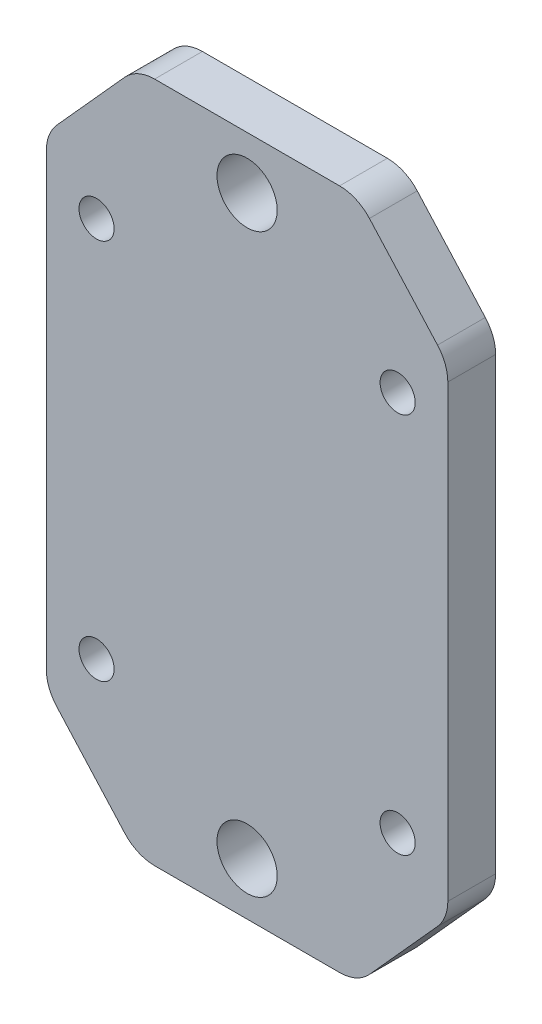
SolidWorks part; units mm, degrees
ref_plane "Front Plane" through (0, 0, 0) normal (0, 0, 1) x (1, 0, 0)
ref_plane "Top Plane" through (0, 0, 0) normal (0, 1, 0) x (1, 0, 0)
ref_plane "Right Plane" through (0, 0, 0) normal (1, 0, 0) x (0, 0, -1)
sketch "Sketch1" plane through (0, 0, 0) normal (0, 0, 1) x (1, 0, 0)
  line L1 (-20, -33.94) -> (20, -33.94)
  line L2 (-20, -33.94) -> (-20, 33.94)
  line L3 (-20, 33.94) -> (20, 33.94)
  line L4 (20, -33.94) -> (20, 33.94)
  line L5 (-20, -33.94) -> (20, 33.94) construction
  line L6 (-20, 33.94) -> (20, -33.94) construction
  circle A0 centre (0, 28.72) radius 3
  circle A1 centre (0, -28.72) radius 3
  circle A2 centre (-15, 19) radius 1.75
  circle A3 centre (-15, -19) radius 1.75
  circle A4 centre (15, 19) radius 1.75
  circle A5 centre (15, -19) radius 1.75
  point P0 (0, 0)
  point P11 (0, 0)
  dimension "D3" = 2
  dimension "D4" = 5.22
  dimension "D1" = 40
  dimension "D2" = 67.88
  dimension "D5" = 5.22
extrude "Boss-Extrude1" add sketch "Sketch1" along normal blind 4.7625
chamfer "Chamfer1" distance 10 angle 42 4 edges at (20, -33.94, 2.3813) (-20, 33.94, 2.3813) (-20, -33.94, 2.3813) (20, 33.94, 2.3813)
fillet "Fillet1" radius 4 8 edges at (-20, 23.94, 2.3813) (-20, -23.94, 2.3813) (-10.996, -33.94, 2.3813) (10.996, -33.94, 2.3813) (20, -23.94, 2.3813) (20, 23.94, 2.3813) (10.996, 33.94, 2.3813) (-10.996, 33.94, 2.3813)
